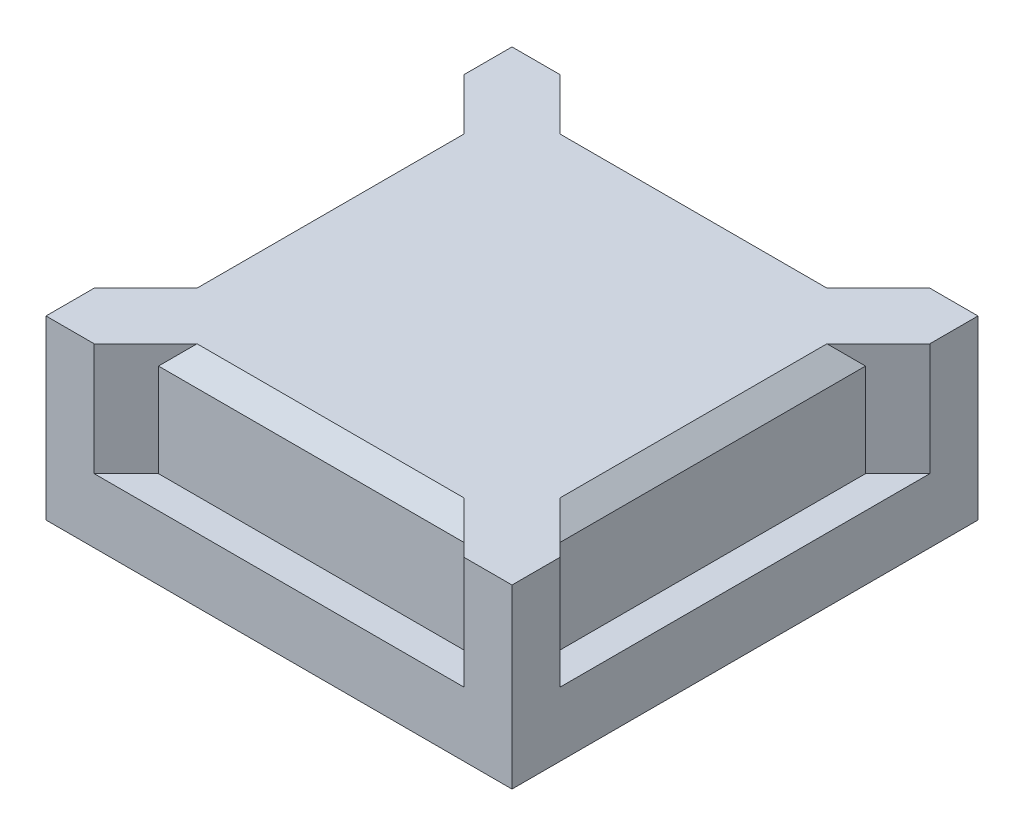
SolidWorks part; units mm, degrees
ref_plane "前视基准面" through (0, 0, 0) normal (0, 0, 1) x (1, 0, 0)
ref_plane "上视基准面" through (0, 0, 0) normal (0, 1, 0) x (1, 0, 0)
ref_plane "右视基准面" through (0, 0, 0) normal (1, 0, 0) x (0, 0, -1)
other "Configuration Table"
sketch "草图1" plane through (0, 0, 0) normal (0, 1, 0) x (1, 0, 0)
  line L1 (2.9, 2.9) -> (-2.9, 2.9)
  line L2 (2.9, 2.9) -> (2.9, -2.9)
  line L3 (2.9, -2.9) -> (-2.9, -2.9)
  line L4 (-2.9, 2.9) -> (-2.9, -2.9)
  line L5 (2.9, 2.9) -> (-2.9, -2.9) construction
  line L6 (2.9, -2.9) -> (-2.9, 2.9) construction
  point P0 (0, 0)
  dimension "D1" = 5.8
  dimension "D2" = 5.8
extrude "凸台-拉伸1" add sketch "草图1" along normal blind 2.2
sketch "草图3" plane through (0, 0, 0) normal (0, -1, 0) x (1, 0, 0)
  line L1 (1.85, 1.5) -> (-1.85, 1.5)
  line L2 (1.85, 1.5) -> (1.85, -1.5)
  line L3 (1.85, -1.5) -> (-1.85, -1.5)
  line L4 (-1.85, 1.5) -> (-1.85, -1.5)
  line L5 (1.85, 1.5) -> (-1.85, -1.5) construction
  line L6 (1.85, -1.5) -> (-1.85, 1.5) construction
  point P0 (0, 0)
  dimension "D1" = 3
  dimension "D2" = 3.7
extrude "切除-拉伸2" cut sketch "草图3" against normal blind 1.75
sketch "草图2" plane through (0, 0, 0) normal (0, -1, 0) x (1, 0, 0)
  line L1 (-2.9, 2.3) -> (-2.5, 2.3) construction
  line L2 (-2.9, 2.3) -> (-2.9, -2.3)
  line L3 (-2.9, -2.3) -> (-2.5, -2.3) construction
  line L4 (-2.5, 2.3) -> (-2.5, -2.3) construction
  line L5 (-2.9, -2.9) -> (-2.9, 2.9) construction
  line L6 (-2.9, -2.9) -> (-2.9, 2.9) construction
  line L7 (-2.9, 2.3) -> (-2.5, 1.9)
  line L8 (-2.5, 1.9) -> (-2.5, -1.9)
  line L20 (-2.5, -1.9) -> (-2.9, -2.3)
  line L21 (-1.9, 2.5) -> (-2.3, 2.9)
  line L22 (2.3, 2.9) -> (-2.3, 2.9)
  line L23 (2.3, 2.9) -> (1.9, 2.5)
  line L24 (1.9, 2.5) -> (-1.9, 2.5)
  line L25 (2.5, 1.9) -> (2.9, 2.3)
  line L26 (2.9, -2.3) -> (2.9, 2.3)
  line L27 (2.9, -2.3) -> (2.5, -1.9)
  line L28 (2.5, -1.9) -> (2.5, 1.9)
  line L29 (1.9, -2.5) -> (2.3, -2.9)
  line L30 (-2.3, -2.9) -> (2.3, -2.9)
  line L31 (-2.3, -2.9) -> (-1.9, -2.5)
  line L32 (-1.9, -2.5) -> (1.9, -2.5)
  point P6 (-2.9, 0)
  point P8 (-2.9, 0)
  point P25 (0, 0)
  point P27 (0, 0)
  dimension "D1" = 0.4
  dimension "D3" = 4.6
  dimension "D2" = 45
  dimension "D4" = 45
  dimension "D5" = 4
extrude "切除-拉伸1" cut sketch "草图2" against normal through all from offset 0.8 offset against normal yes
chamfer "倒角1" distance 0.24 angle 45 4 edges at (-2.5, 2.2, 0) (0, 2.2, 2.5) (2.5, 2.2, 0) (0, 2.2, -2.5)
